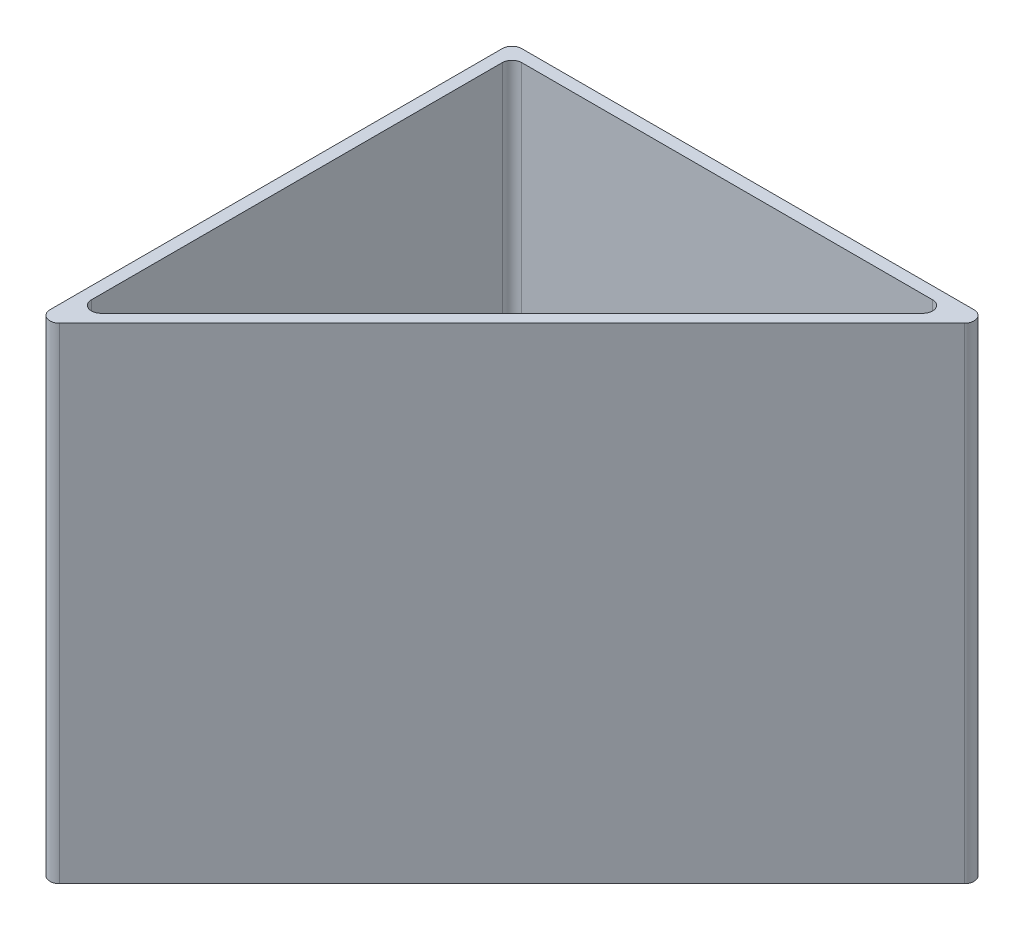
SolidWorks part; units mm, degrees
material "2219-O"
ref_plane "Front Plane" through (0, 0, 0) normal (0, 0, 1) x (1, 0, 0)
ref_plane "Top Plane" through (0, 0, 0) normal (0, 1, 0) x (1, 0, 0)
ref_plane "Right Plane" through (0, 0, 0) normal (1, 0, 0) x (0, 0, -1)
sketch "Sketch1" plane through (0, 0, 0) normal (0, 1, 0) x (1, 0, 0)
  line L0 (0, 0) -> (0, -100)
  line L1 (0, -100) -> (100, 0)
  line L2 (100, 0) -> (0, 0)
  dimension "D2" = 100
extrude "Boss-Extrude1" add sketch "Sketch1" along normal blind 100
shell "Shell1" thickness 2.5
sketch "Sketch3" plane through (0, 2.5, 0) normal (0, 1, 0) x (1, 0, 0)
  line L0 (5, -5) -> (35360.3391, -35360.3391) construction
  line L1 (2.5, -93.9645) -> (93.9645, -2.5) construction
  line L2 (14.1421, -14.1421) -> (14.1421, -57.5736) construction
  line L4 (0, -100) -> (100, 0) construction
  line L5 (14.1421, -14.1421) -> (57.5736, -14.1421) construction
  point P5 (48.2322, -48.2322)
  dimension "D1" = 20
  dimension "D2" = 20
hole_wizard "Tap Drill for M5x0.8 Tap1" positions "3DSketch1" profile "Sketch4" hole size "M5x0.8" standard "ANSI Metric" end condition through all
sketch3d "3DSketch1"
  point P0 (14.1421, 2.5, 14.1421)
  point P3 (14.1421, 2.5, 57.5736)
  point P6 (57.5736, 2.5, 14.1421)
sketch "Sketch4" plane through (14.1421, 2.5, 14.1421) normal (1, 0, 0) x (0, 0, 1)
  line L0 (0, 0) -> (0, 2.5)
  line L1 (0, 2.5) -> (2.1, 2.5)
  line L2 (2.1, 2.5) -> (2.1, 0)
  line L5 (2.1, 0) -> (0, 0)
  line L11 (0, -6.35) -> (0, 107.95) construction
  dimension "Thru Hole Dia." = 4.2
  dimension "Thru Hole Depth" = 2.5
fillet "Fillet1" radius 2 6 edges at (100, 50, 0) (0, 50, 100) (0, 50, 0) (93.9645, 51.25, 2.5) (2.5, 51.25, 2.5) (2.5, 51.25, 93.9645)
equation "\"half_plate_thickness\"= 0.5cm'Total plate thickness = 1 cm"
equation "\"plate_length\"= 60cm'Parallel to x-axis"
equation "\"plate_width\"= 45cm'Parallel to z-axis"
equation "\"electronics_box_length\"= 10cm'Parallel to x-axis"
equation "\"wall_width\"= 2cm'Same value for wall_length"
equation "\"eds_radius\"= 1mm"
equation "\"eds_spacing\"= 15mm"
equation "\"general_tolerance\"= 0.5mm"
equation "\"eds_count\"= 36"
equation "\"plate_fillet_radius\"= 10mm"
equation "\"tooth_height\"= 1cm"
equation "\"tooth_offset\"= 0.5cm"
equation "\"tooth_patch_width\"= 7.5cm"
equation "\"D2@Sketch1\"=\"electronics_box_length\""
equation "\"D1@Sketch3\"=\"wall_width\""
equation "\"D2@Sketch3\"=\"wall_width\""
